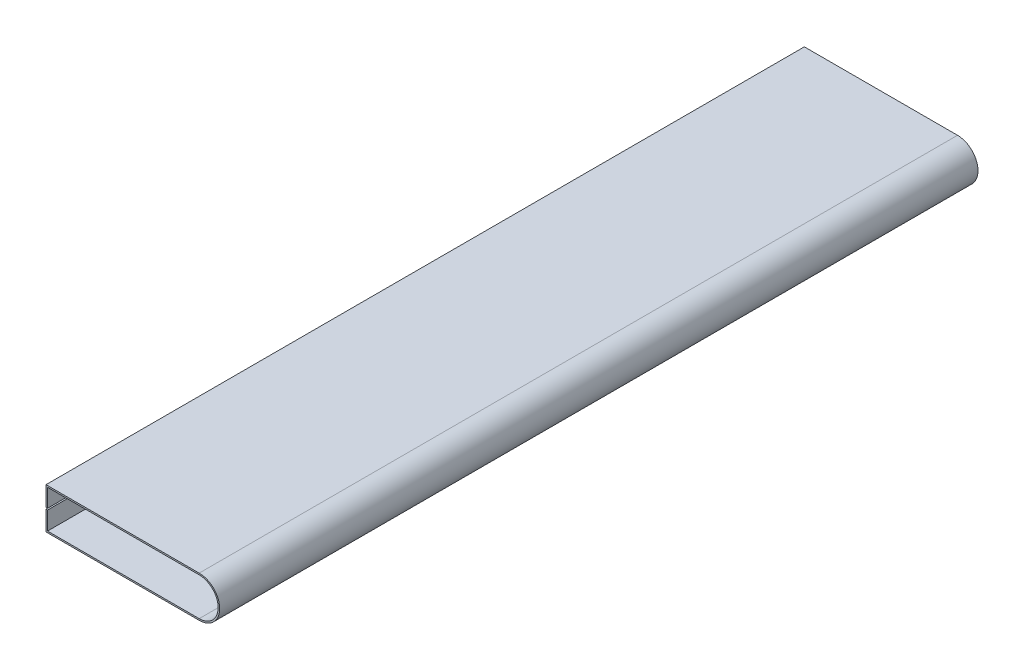
SolidWorks part; units mm, degrees
material "6061 Alloy"
ref_plane "Front Plane" through (0, 0, 0) normal (0, 0, 1) x (1, 0, 0)
ref_plane "Top Plane" through (0, 0, 0) normal (0, 1, 0) x (1, 0, 0)
ref_plane "Right Plane" through (0, 0, 0) normal (1, 0, 0) x (0, 0, -1)
sketch "Sketch1" plane through (0, 0, 0) normal (0, 0, 1) x (1, 0, 0)
  line L0 (-119.957, 72.1811) -> (82.043, 72.1811)
  line L1 (-117.957, 70.1811) -> (82.043, 70.1811)
  line L2 (-117.957, 70.1811) -> (-117.957, 46.1811)
  line L3 (-117.957, 20.1811) -> (82.043, 20.1811)
  line L5 (-119.957, 18.1811) -> (82.043, 18.1811)
  line L6 (-119.957, 72.1811) -> (-119.957, 46.1811)
  line L7 (82.043, 45.1811) -> (-188.4, 45.1811) construction
  line L8 (-117.957, 46.1811) -> (-119.957, 46.1811)
  line L9 (-117.957, 44.1811) -> (-119.957, 44.1811)
  line L10 (-119.957, 44.1811) -> (-119.957, 18.1811)
  line L11 (-119.957, 72.1811) -> (-119.957, 18.1811) construction
  line L12 (-117.957, 44.1811) -> (-117.957, 20.1811)
  line L13 (-117.957, 70.1811) -> (-117.957, 20.1811) construction
  arc A0 (82.043, 70.1811) -> (82.043, 20.1811) centre (82.043, 45.1811) cw
  arc A1 (82.043, 72.1811) -> (82.043, 18.1811) centre (82.043, 45.1811) cw
  point P17 (82.043, 45.1811)
  dimension "D3" = 1
  dimension "D1" = 200
  dimension "D2" = 50
  dimension "D4" = 2
  dimension "D5" = 1
extrude "Boss-Extrude1" add sketch "Sketch1" against normal blind 1000
ref_point "Point1"
